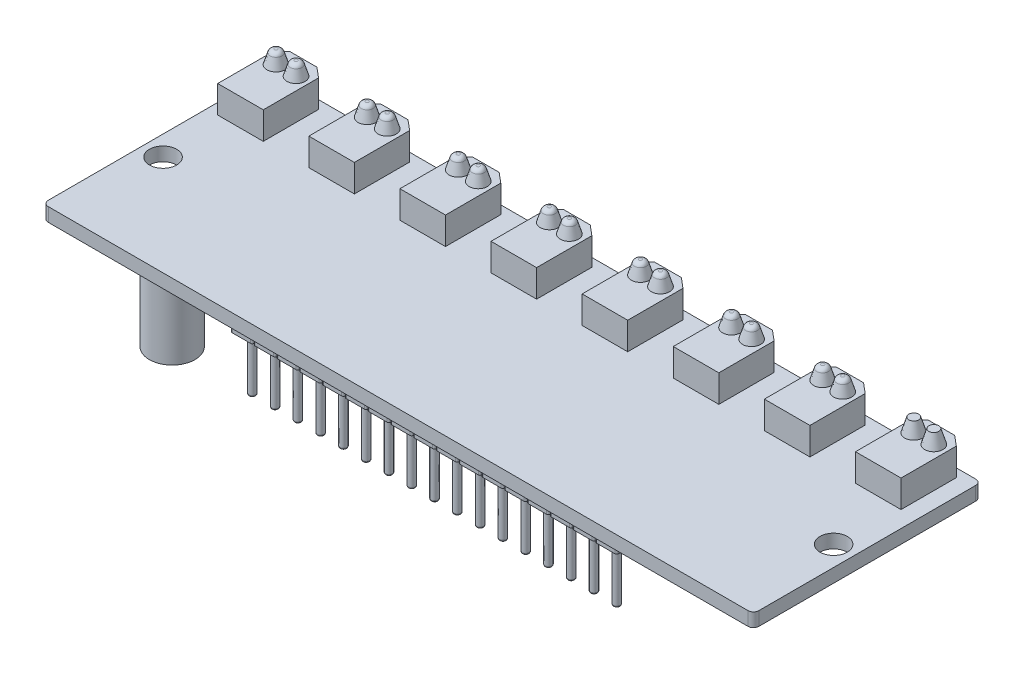
SolidWorks part; units mm, degrees
ref_plane "Front Plane" through (0, 0, 0) normal (0, 0, 1) x (1, 0, 0)
ref_plane "Top Plane" through (0, 0, 0) normal (0, 1, 0) x (1, 0, 0)
ref_plane "Right Plane" through (0, 0, 0) normal (1, 0, 0) x (0, 0, -1)
sketch "Sketch1" plane through (0, 0, 0) normal (0, 1, 0) x (1, 0, 0)
  line L1 (39, -12.5) -> (-39, -12.5)
  line L2 (39, -12.5) -> (39, 12.5)
  line L3 (39, 12.5) -> (-39, 12.5)
  line L4 (-39, -12.5) -> (-39, 12.5)
  line L5 (39, -12.5) -> (-39, 12.5) construction
  line L6 (39, 12.5) -> (-39, -12.5) construction
  point P0 (0, 0)
  dimension "D1" = 25
  dimension "D2" = 78
extrude "Boss-Extrude1" add sketch "Sketch1" along normal blind 1.5
fillet "Fillet1" radius 0.6 4 edges at (39, 0.75, 12.5) (39, 0.75, -12.5) (-39, 0.75, -12.5) (-39, 0.75, 12.5)
sketch "Sketch2" plane through (0, 1.5, 0) normal (0, 1, 0) x (1, 0, 0)
  line L0 (0, 0) -> (0, 12.5) construction
  line L1 (38.4, 12.5) -> (-38.4, 12.5) construction
  line L2 (-39, 11.9) -> (-39, -11.9) construction
  circle A0 centre (-36.8, -1.5) radius 1.5
  circle A1 centre (36.8, -1.5) radius 1.5
  dimension "D1" = 3
  dimension "D2" = 14
  dimension "D3" = 2.2
extrude "Cut-Extrude1" cut sketch "Sketch2" against normal blind 1.5
sketch "Sketch3" plane through (0, 1.5, 0) normal (0, 1, 0) x (1, 0, 0)
  line L0 (38.4, 12.5) -> (-38.4, 12.5) construction
  line L1 (-36.8668, 12.5) -> (-33.914, 12.5)
  line L2 (-37.8, 11.5668) -> (-37.8, 5.5)
  line L3 (-37.8, 5.5) -> (-32.8, 5.5)
  line L4 (-32.8, 11.5668) -> (-32.8, 5.5)
  line L5 (-37.4112, 11.9556) -> (-32.8, 5.5) construction
  line L6 (-37.8, 5.5) -> (-33.217, 11.9161) construction
  line L7 (-39, 11.9) -> (-39, -11.9) construction
  line L8 (-36.8668, 12.5) -> (-37.8, 11.5668)
  line L9 (-33.914, 12.5) -> (-32.8, 11.5668)
  line L10 (-22.8, 11.5668) -> (-22.8, 5.5)
  line L11 (-23.914, 12.5) -> (-22.8, 11.5668)
  line L12 (-26.8668, 12.5) -> (-23.914, 12.5)
  line L13 (-26.8668, 12.5) -> (-27.8, 11.5668)
  line L14 (-27.8, 11.5668) -> (-27.8, 5.5)
  line L15 (-27.8, 5.5) -> (-22.8, 5.5)
  line L16 (-12.8, 11.5668) -> (-12.8, 5.5)
  line L17 (-13.914, 12.5) -> (-12.8, 11.5668)
  line L18 (-16.8668, 12.5) -> (-13.914, 12.5)
  line L19 (-16.8668, 12.5) -> (-17.8, 11.5668)
  line L20 (-17.8, 11.5668) -> (-17.8, 5.5)
  line L21 (-17.8, 5.5) -> (-12.8, 5.5)
  line L22 (-2.8, 11.5668) -> (-2.8, 5.5)
  line L23 (-3.914, 12.5) -> (-2.8, 11.5668)
  line L24 (-6.8668, 12.5) -> (-3.914, 12.5)
  line L25 (-6.8668, 12.5) -> (-7.8, 11.5668)
  line L26 (-7.8, 11.5668) -> (-7.8, 5.5)
  line L27 (-7.8, 5.5) -> (-2.8, 5.5)
  line L28 (7.2, 11.5668) -> (7.2, 5.5)
  line L29 (6.086, 12.5) -> (7.2, 11.5668)
  line L30 (3.1332, 12.5) -> (6.086, 12.5)
  line L31 (3.1332, 12.5) -> (2.2, 11.5668)
  line L32 (2.2, 11.5668) -> (2.2, 5.5)
  line L33 (2.2, 5.5) -> (7.2, 5.5)
  line L34 (17.2, 11.5668) -> (17.2, 5.5)
  line L35 (16.086, 12.5) -> (17.2, 11.5668)
  line L36 (13.1332, 12.5) -> (16.086, 12.5)
  line L37 (13.1332, 12.5) -> (12.2, 11.5668)
  line L38 (12.2, 11.5668) -> (12.2, 5.5)
  line L39 (12.2, 5.5) -> (17.2, 5.5)
  line L40 (27.2, 11.5668) -> (27.2, 5.5)
  line L41 (26.086, 12.5) -> (27.2, 11.5668)
  line L42 (23.1332, 12.5) -> (26.086, 12.5)
  line L43 (23.1332, 12.5) -> (22.2, 11.5668)
  line L44 (22.2, 11.5668) -> (22.2, 5.5)
  line L45 (22.2, 5.5) -> (27.2, 5.5)
  line L46 (37.2, 11.5668) -> (37.2, 5.5)
  line L47 (36.086, 12.5) -> (37.2, 11.5668)
  line L48 (33.1332, 12.5) -> (36.086, 12.5)
  line L49 (33.1332, 12.5) -> (32.2, 11.5668)
  line L50 (32.2, 11.5668) -> (32.2, 5.5)
  line L51 (32.2, 5.5) -> (37.2, 5.5)
  point P0 (-35.3, 9)
  dimension "D1" = 5
  dimension "D2" = 7
  dimension "D3" = 0
  dimension "D4" = 1.2
  dimension "D5" = 8
extrude "Boss-Extrude2" add sketch "Sketch3" along normal blind 3
sketch "Sketch4" plane through (0, 4.5, 0) normal (0, 1, 0) x (1, 0, 0)
  line L0 (-37.8, 11.5668) -> (-37.8, 5.5) construction
  line L1 (-32.8, 5.5) -> (-32.8, 11.5668) construction
  line L2 (-37.8, 5.5) -> (-32.8, 5.5) construction
  line L3 (-37.8, 5.5) -> (-32.8, 5.5) construction
  circle A0 centre (-36.4, 10.4996) radius 1
  circle A1 centre (-34.2, 10.4996) radius 1
  circle A2 centre (-26.4, 10.4996) radius 1 construction
  circle A3 centre (-24.2, 10.4996) radius 1 construction
  circle A4 centre (-16.4, 10.4996) radius 1 construction
  circle A5 centre (-14.2, 10.4996) radius 1 construction
  circle A6 centre (-6.4, 10.4996) radius 1 construction
  circle A7 centre (-4.2, 10.4996) radius 1 construction
  circle A8 centre (3.6, 10.4996) radius 1 construction
  circle A9 centre (5.8, 10.4996) radius 1 construction
  circle A10 centre (13.6, 10.4996) radius 1 construction
  circle A11 centre (15.8, 10.4996) radius 1 construction
  circle A12 centre (23.6, 10.4996) radius 1 construction
  circle A13 centre (25.8, 10.4996) radius 1 construction
  circle A14 centre (33.6, 10.4996) radius 1 construction
  circle A15 centre (35.8, 10.4996) radius 1 construction
  circle A16 centre (-26.4, 10.4996) radius 1
  circle A17 centre (-24.2, 10.4996) radius 1
  circle A18 centre (-16.4, 10.4996) radius 1
  circle A19 centre (-14.2, 10.4996) radius 1
  circle A20 centre (-6.4, 10.4996) radius 1
  circle A21 centre (-4.2, 10.4996) radius 1
  circle A22 centre (3.6, 10.4996) radius 1
  circle A23 centre (5.8, 10.4996) radius 1
  circle A24 centre (13.6, 10.4996) radius 1
  circle A25 centre (15.8, 10.4996) radius 1
  circle A26 centre (23.6, 10.4996) radius 1
  circle A27 centre (25.8, 10.4996) radius 1
  circle A28 centre (33.6, 10.4996) radius 1
  circle A29 centre (35.8, 10.4996) radius 1
  dimension "D1" = 2
  dimension "D2" = 2
  dimension "D5" = 4.9996
  dimension "D6" = 4.9996
  dimension "D3" = 1.4
  dimension "D4" = 1.4
  dimension "D7" = 8
  dimension "D8" = 8
extrude "Boss-Extrude7" add sketch "Sketch4" along normal blind 1.5 draft 17
fillet "Fillet4" radius 0.5 14 edges at (-36.4, 6, -9.9582) (-34.2, 6, -9.9582) (-26.4, 6, -9.9582) (-24.2, 6, -9.9582) (-16.4, 6, -9.9582) (-14.2, 6, -9.9582) (-6.4, 6, -9.9582) (-4.2, 6, -9.9582) (25.8, 6, -9.9582) (23.6, 6, -9.9582) (15.8, 6, -9.9582) (13.6, 6, -9.9582) (5.8, 6, -9.9582) (3.6, 6, -9.9582)
sketch "Sketch5" plane through (0, 0, 0) normal (0, -1, 0) x (1, 0, 0)
  line L0 (38.4, -12.5) -> (-38.4, -12.5) construction
  line L1 (-22.5, 10.9) -> (-20.1, 10.9)
  line L2 (-22.5, 10.9) -> (-22.5, 8.5)
  line L3 (-22.5, 8.5) -> (-20.1, 8.5)
  line L4 (-20.1, 10.9) -> (-20.1, 8.5)
  line L5 (-22.5, 10.9) -> (-20.1, 8.5) construction
  line L6 (-22.5, 8.5) -> (-20.1, 10.9) construction
  line L7 (-20, 10.9) -> (-20, 8.5)
  line L8 (-17.6, 10.9) -> (-17.6, 8.5)
  line L9 (-20, 8.5) -> (-17.6, 8.5)
  line L10 (-17.5, 10.9) -> (-17.5, 8.5)
  line L11 (-15.1, 10.9) -> (-15.1, 8.5)
  line L12 (-17.5, 8.5) -> (-15.1, 8.5)
  line L13 (-15, 10.9) -> (-15, 8.5)
  line L14 (-12.6, 10.9) -> (-12.6, 8.5)
  line L15 (-15, 8.5) -> (-12.6, 8.5)
  line L16 (-12.5, 10.9) -> (-12.5, 8.5)
  line L17 (-10.1, 10.9) -> (-10.1, 8.5)
  line L18 (-12.5, 8.5) -> (-10.1, 8.5)
  line L19 (-10, 10.9) -> (-10, 8.5)
  line L20 (-7.6, 10.9) -> (-7.6, 8.5)
  line L21 (-10, 8.5) -> (-7.6, 8.5)
  line L22 (-7.5, 10.9) -> (-7.5, 8.5)
  line L23 (-5.1, 10.9) -> (-5.1, 8.5)
  line L24 (-7.5, 8.5) -> (-5.1, 8.5)
  line L25 (-5, 10.9) -> (-5, 8.5)
  line L26 (-2.6, 10.9) -> (-2.6, 8.5)
  line L27 (-5, 8.5) -> (-2.6, 8.5)
  line L28 (-2.5, 10.9) -> (-2.5, 8.5)
  line L29 (-0.1, 10.9) -> (-0.1, 8.5)
  line L30 (-2.5, 8.5) -> (-0.1, 8.5)
  line L31 (0, 10.9) -> (0, 8.5)
  line L32 (2.4, 10.9) -> (2.4, 8.5)
  line L33 (0, 8.5) -> (2.4, 8.5)
  line L34 (2.5, 10.9) -> (2.5, 8.5)
  line L35 (4.9, 10.9) -> (4.9, 8.5)
  line L36 (2.5, 8.5) -> (4.9, 8.5)
  line L37 (5, 10.9) -> (5, 8.5)
  line L38 (7.4, 10.9) -> (7.4, 8.5)
  line L39 (5, 8.5) -> (7.4, 8.5)
  line L40 (7.5, 10.9) -> (7.5, 8.5)
  line L41 (9.9, 10.9) -> (9.9, 8.5)
  line L42 (7.5, 8.5) -> (9.9, 8.5)
  line L43 (10, 10.9) -> (10, 8.5)
  line L44 (12.4, 10.9) -> (12.4, 8.5)
  line L45 (10, 8.5) -> (12.4, 8.5)
  line L46 (12.5, 10.9) -> (12.5, 8.5)
  line L47 (14.9, 10.9) -> (14.9, 8.5)
  line L48 (12.5, 8.5) -> (14.9, 8.5)
  line L49 (15, 10.9) -> (15, 8.5)
  line L50 (17.4, 10.9) -> (17.4, 8.5)
  line L51 (15, 8.5) -> (17.4, 8.5)
  line L52 (17.5, 10.9) -> (17.5, 8.5)
  line L53 (19.9, 10.9) -> (19.9, 8.5)
  line L54 (17.5, 8.5) -> (19.9, 8.5)
  line L55 (20, 10.9) -> (20, 8.5)
  line L56 (22.4, 10.9) -> (22.4, 8.5)
  line L57 (20, 8.5) -> (22.4, 8.5)
  line L58 (-20, 10.9) -> (-20, 8.5)
  line L59 (-17.6, 10.9) -> (-17.6, 8.5)
  line L60 (-20, 8.5) -> (-17.6, 8.5)
  line L61 (-20, 10.9) -> (-17.6, 10.9)
  line L62 (-17.5, 10.9) -> (-17.5, 8.5)
  line L63 (-15.1, 10.9) -> (-15.1, 8.5)
  line L64 (-17.5, 8.5) -> (-15.1, 8.5)
  line L65 (-17.5, 10.9) -> (-15.1, 10.9)
  line L66 (-15, 10.9) -> (-15, 8.5)
  line L67 (-12.6, 10.9) -> (-12.6, 8.5)
  line L68 (-15, 8.5) -> (-12.6, 8.5)
  line L69 (-15, 10.9) -> (-12.6, 10.9)
  line L70 (-12.5, 10.9) -> (-12.5, 8.5)
  line L71 (-10.1, 10.9) -> (-10.1, 8.5)
  line L72 (-12.5, 8.5) -> (-10.1, 8.5)
  line L73 (-12.5, 10.9) -> (-10.1, 10.9)
  line L74 (-10, 10.9) -> (-10, 8.5)
  line L75 (-7.6, 10.9) -> (-7.6, 8.5)
  line L76 (-10, 8.5) -> (-7.6, 8.5)
  line L77 (-10, 10.9) -> (-7.6, 10.9)
  line L78 (-7.5, 10.9) -> (-7.5, 8.5)
  line L79 (-5.1, 10.9) -> (-5.1, 8.5)
  line L80 (-7.5, 8.5) -> (-5.1, 8.5)
  line L81 (-7.5, 10.9) -> (-5.1, 10.9)
  line L82 (-5, 10.9) -> (-5, 8.5)
  line L83 (-2.6, 10.9) -> (-2.6, 8.5)
  line L84 (-5, 8.5) -> (-2.6, 8.5)
  line L85 (-5, 10.9) -> (-2.6, 10.9)
  line L86 (-2.5, 10.9) -> (-2.5, 8.5)
  line L87 (-0.1, 10.9) -> (-0.1, 8.5)
  line L88 (-2.5, 8.5) -> (-0.1, 8.5)
  line L89 (-2.5, 10.9) -> (-0.1, 10.9)
  line L90 (0, 10.9) -> (0, 8.5)
  line L91 (2.4, 10.9) -> (2.4, 8.5)
  line L92 (0, 8.5) -> (2.4, 8.5)
  line L93 (0, 10.9) -> (2.4, 10.9)
  line L94 (2.5, 10.9) -> (2.5, 8.5)
  line L95 (4.9, 10.9) -> (4.9, 8.5)
  line L96 (2.5, 8.5) -> (4.9, 8.5)
  line L97 (2.5, 10.9) -> (4.9, 10.9)
  line L98 (5, 10.9) -> (5, 8.5)
  line L99 (7.4, 10.9) -> (7.4, 8.5)
  line L100 (5, 8.5) -> (7.4, 8.5)
  line L101 (5, 10.9) -> (7.4, 10.9)
  line L102 (7.5, 10.9) -> (7.5, 8.5)
  line L103 (9.9, 10.9) -> (9.9, 8.5)
  line L104 (7.5, 8.5) -> (9.9, 8.5)
  line L105 (7.5, 10.9) -> (9.9, 10.9)
  line L106 (10, 10.9) -> (10, 8.5)
  line L107 (12.4, 10.9) -> (12.4, 8.5)
  line L108 (10, 8.5) -> (12.4, 8.5)
  line L109 (10, 10.9) -> (12.4, 10.9)
  line L110 (12.5, 10.9) -> (12.5, 8.5)
  line L111 (14.9, 10.9) -> (14.9, 8.5)
  line L112 (12.5, 8.5) -> (14.9, 8.5)
  line L113 (12.5, 10.9) -> (14.9, 10.9)
  line L114 (15, 10.9) -> (15, 8.5)
  line L115 (17.4, 10.9) -> (17.4, 8.5)
  line L116 (15, 8.5) -> (17.4, 8.5)
  line L117 (15, 10.9) -> (17.4, 10.9)
  line L118 (17.5, 10.9) -> (17.5, 8.5)
  line L119 (19.9, 10.9) -> (19.9, 8.5)
  line L120 (17.5, 8.5) -> (19.9, 8.5)
  line L121 (17.5, 10.9) -> (19.9, 10.9)
  line L122 (20, 10.9) -> (20, 8.5)
  line L123 (22.4, 10.9) -> (22.4, 8.5)
  line L124 (20, 8.5) -> (22.4, 8.5)
  line L125 (20, 10.9) -> (22.4, 10.9)
  line L126 (-39, -11.9) -> (-39, 11.9) construction
  point P0 (-21.3, 9.7)
  dimension "D1" = 2.4
  dimension "D2" = 2.4
  dimension "D3" = 21
  dimension "D6" = 16.5
  dimension "D4" = 18
  dimension "D5" = 18
extrude "Boss-Extrude12" add sketch "Sketch5" along normal blind 2 contours L65 L10 L12 L11 | L69 L13 L15 L14 | L73 L16 L18 L17 | L77 L19 L21 L20 | L81 L22 L24 L23 | L61 L7 L9 L8 | L85 L25 L27 L26 | L89 L28 L30 L29 | L93 L31 L33 L32 | L97 L34 L36 L35 | L101 L37 L39 L38 | L105 L40 L42 L41 | L109 L43 L45 L44 | L113 L46 L48 L47 | L117 L49 L51 L50 | L121 L52 L54 L53 | L125 L55 L57 L56
sketch "Sketch6" plane through (0, -2, 0) normal (0, -1, 0) x (1, 0, 0)
  line L0 (-20, 8.5) -> (-17.6, 8.5) construction
  line L1 (-20, 10.9) -> (-17.6, 10.9) construction
  circle A0 centre (-18.8, 9.7) radius 0.375
  circle A1 centre (-16.3, 9.7) radius 0.375
  circle A2 centre (-13.8, 9.7) radius 0.375
  circle A3 centre (-11.3, 9.7) radius 0.375
  circle A4 centre (-8.8, 9.7) radius 0.375
  circle A5 centre (-6.3, 9.7) radius 0.375
  circle A6 centre (-3.8, 9.7) radius 0.375
  circle A7 centre (-1.3, 9.7) radius 0.375
  circle A8 centre (1.2, 9.7) radius 0.375
  circle A9 centre (3.7, 9.7) radius 0.375
  circle A10 centre (6.2, 9.7) radius 0.375
  circle A11 centre (8.7, 9.7) radius 0.375
  circle A12 centre (11.2, 9.7) radius 0.375
  circle A13 centre (13.7, 9.7) radius 0.375
  circle A14 centre (16.2, 9.7) radius 0.375
  circle A15 centre (18.7, 9.7) radius 0.375
  circle A16 centre (21.2, 9.7) radius 0.375
  point P4 (-18.8, 10.9)
  dimension "D1" = 1.2
  dimension "D2" = 1.2
  dimension "D3" = 0.75
  dimension "D4" = 17
extrude "Boss-Extrude13" add sketch "Sketch6" along normal blind 6
fillet "Fillet5" radius 0.2 4 edges at (-17.6, -1, 10.9) (-17.6, -1, 8.5) (-20, -1, 8.5) (-20, -1, 10.9)
fillet "Fillet7" radius 0.2 64 edges at (22.4, -1, 8.5) (20, -1, 8.5) (19.9, -1, 8.5) (17.5, -1, 8.5) (17.4, -1, 8.5) (15, -1, 8.5) (14.9, -1, 8.5) (12.5, -1, 8.5) (12.4, -1, 8.5) (10, -1, 8.5) (9.9, -1, 8.5) (7.5, -1, 8.5) (7.4, -1, 8.5) (5, -1, 8.5) (4.9, -1, 8.5) (2.5, -1, 8.5) (2.4, -1, 8.5) (0, -1, 8.5) (-0.1, -1, 8.5) (-2.5, -1, 8.5) (-2.6, -1, 8.5) (-5, -1, 8.5) (-5.1, -1, 8.5) (-7.5, -1, 8.5) (-7.6, -1, 8.5) (-10, -1, 8.5) (-10.1, -1, 8.5) (-12.5, -1, 8.5) (-12.6, -1, 8.5) (-15, -1, 8.5) (-15.1, -1, 8.5) (-17.5, -1, 8.5) (22.4, -1, 10.9) (20, -1, 10.9) (19.9, -1, 10.9) (17.5, -1, 10.9) (17.4, -1, 10.9) (15, -1, 10.9) (14.9, -1, 10.9) (12.5, -1, 10.9) (12.4, -1, 10.9) (10, -1, 10.9) (9.9, -1, 10.9) (7.5, -1, 10.9) (7.4, -1, 10.9) (5, -1, 10.9) (4.9, -1, 10.9) (2.5, -1, 10.9) (2.4, -1, 10.9) (0, -1, 10.9) (-0.1, -1, 10.9) (-2.5, -1, 10.9) (-2.6, -1, 10.9) (-5, -1, 10.9) (-5.1, -1, 10.9) (-7.5, -1, 10.9) (-7.6, -1, 10.9) (-10, -1, 10.9) (-10.1, -1, 10.9) (-12.5, -1, 10.9) (-12.6, -1, 10.9) (-15, -1, 10.9) (-15.1, -1, 10.9) (-17.5, -1, 10.9)
fillet "Fillet8" radius 0.2 17 edges at (21.2, -8, 9.325) (18.7, -8, 9.325) (16.2, -8, 9.325) (13.7, -8, 9.325) (11.2, -8, 9.325) (8.7, -8, 9.325) (6.2, -8, 9.325) (3.7, -8, 9.325) (1.2, -8, 9.325) (-1.3, -8, 9.325) (-3.8, -8, 9.325) (-6.3, -8, 9.325) (-8.8, -8, 9.325) (-11.3, -8, 9.325) (-13.8, -8, 9.325) (-16.3, -8, 9.325) (-18.8, -8, 9.325)
sketch "Sketch7" plane through (0, 0, 0) normal (0, -1, 0) x (1, 0, 0)
  circle A0 centre (-29.8, 7.5) radius 2.5
  circle A1 centre (-36.8, 1.5) radius 1.5 construction
  dimension "D2" = 7
  dimension "D3" = 5
  dimension "D1" = 6
extrude "Boss-Extrude14" add sketch "Sketch7" along normal blind 10
